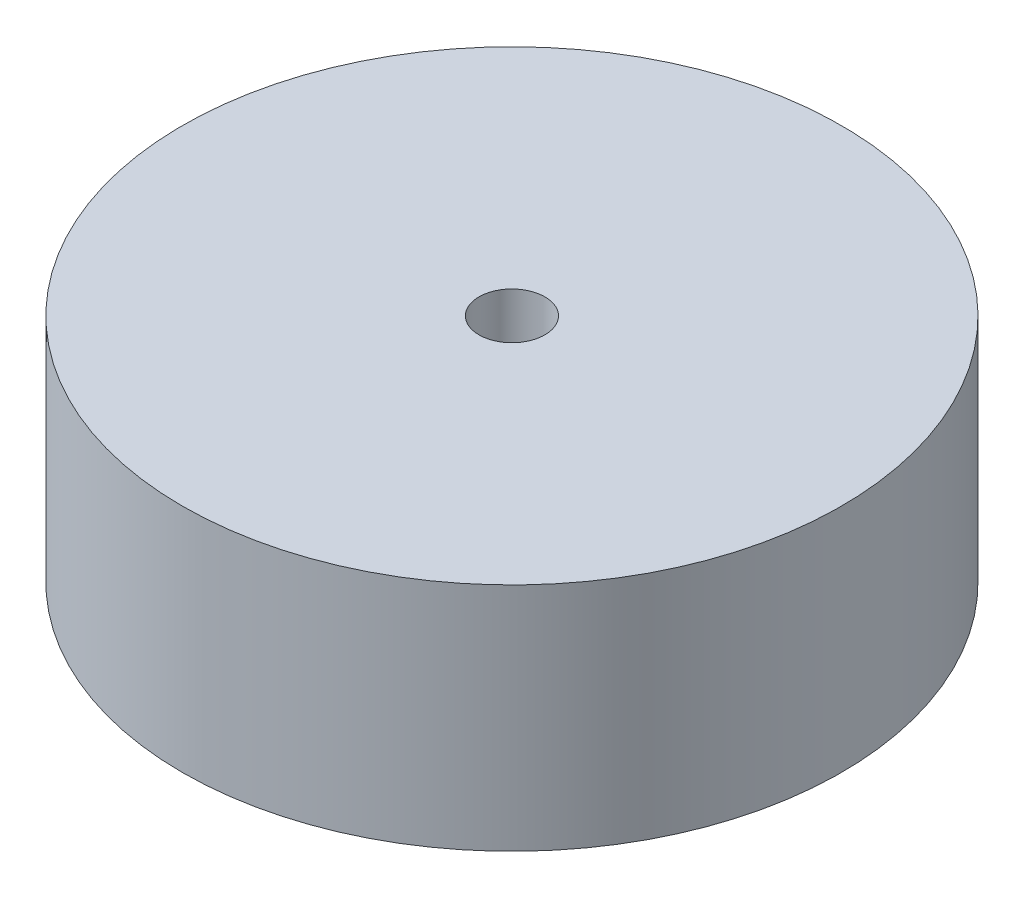
SolidWorks part; units mm, degrees
ref_plane "Front Plane" through (0, 0, 0) normal (0, 0, 1) x (1, 0, 0)
ref_plane "Top Plane" through (0, 0, 0) normal (0, 1, 0) x (1, 0, 0)
ref_plane "Right Plane" through (0, 0, 0) normal (1, 0, 0) x (0, 0, -1)
sketch "Sketch1" plane through (0, 0, 0) normal (0, 1, 0) x (1, 0, 0)
  circle A0 centre (0, 0) radius 10
  circle A1 centre (0, 0) radius 1
  dimension "D1" = 20
  dimension "D2" = 2
extrude "Boss-Extrude1" add sketch "Sketch1" along normal blind 7
